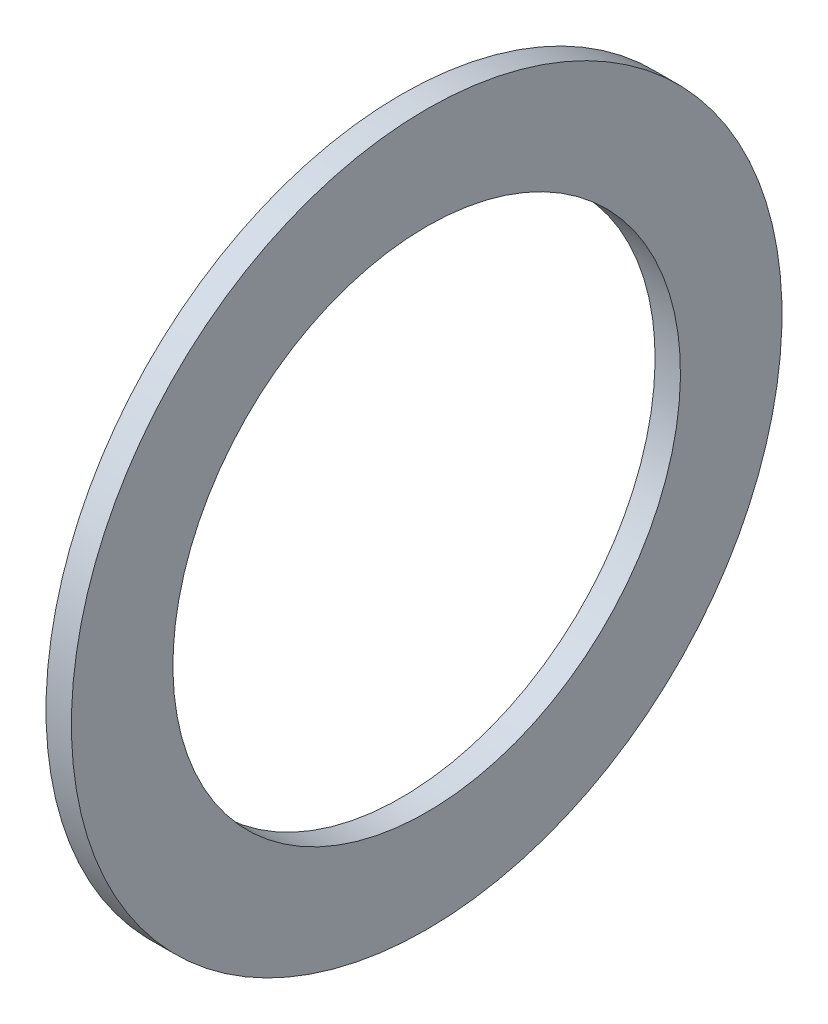
SolidWorks part; units mm, degrees
ref_plane "Front Plane" through (0, 0, 0) normal (0, 0, 1) x (1, 0, 0)
ref_plane "Top Plane" through (0, 0, 0) normal (0, 1, 0) x (1, 0, 0)
ref_plane "Right Plane" through (0, 0, 0) normal (1, 0, 0) x (0, 0, -1)
sketch "Sketch1" plane through (0, 0, 0) normal (0, 0, 1) x (1, 0, 0)
  line L0 (0, 0) -> (3000, 0) construction
  line L1 (1450, 500) -> (1450, 700)
  line L2 (1450, 700) -> (1500, 700)
  line L3 (1500, 700) -> (1500, 500)
  line L4 (1500, 500) -> (1450, 500)
revolve "Revolve1" add sketch "Sketch1" angle 360 about L0
